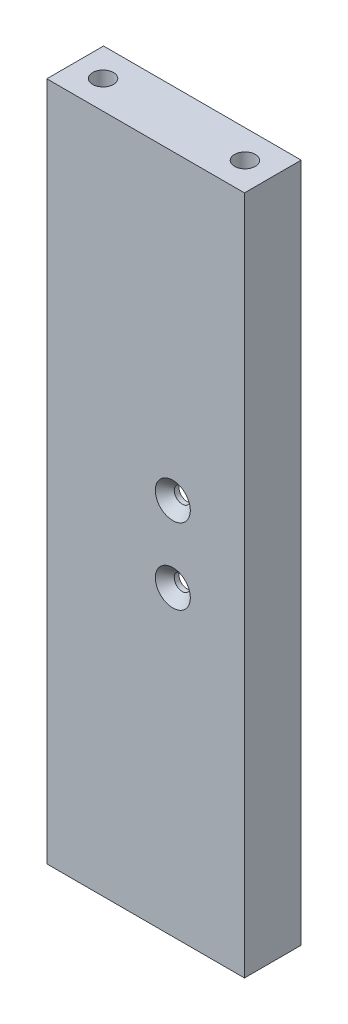
SolidWorks part; units mm, degrees
ref_plane "Front Plane" through (0, 0, 0) normal (0, 0, 1) x (1, 0, 0)
ref_plane "Top Plane" through (0, 0, 0) normal (0, 1, 0) x (1, 0, 0)
ref_plane "Right Plane" through (0, 0, 0) normal (1, 0, 0) x (0, 0, -1)
sketch "Sketch1" plane through (0, 0, 0) normal (0, 0, 1) x (1, 0, 0)
  line L1 (-20.9, 0) -> (20.9, 0)
  line L2 (-20.9, 0) -> (-20.9, 143.8)
  line L3 (-20.9, 143.8) -> (20.9, 143.8)
  line L4 (20.9, 0) -> (20.9, 143.8)
  point P4 (0, 0)
  dimension "D1" = 143.8
  dimension "D2" = 41.8
extrude "Boss-Extrude1" add sketch "Sketch1" against normal blind 12
shell "Shell1" thickness 7
sketch "Sketch2" plane through (0, 143.8, 0) normal (0, 1, 0) x (1, 0, 0)
  line L0 (0, 12) -> (0, 0) construction
  line L1 (20.9, 12) -> (-20.9, 12) construction
  line L5 (20.9, 0) -> (-20.9, 0) construction
  circle A1 centre (-15, 6) radius 2.2
  circle A2 centre (15, 6) radius 2.2
  dimension "D1" = 4.4
  dimension "D2" = 6
  dimension "D3" = 15
extrude "Cut-Extrude1" cut sketch "Sketch2" against normal blind 5.2
ref_plane "Plane1" through (0, 71.9, 0) normal (0, 1, 0) x (1, 0, 0)
mirror "Mirror1" about plane through (0, 71.9, 0) normal (0, 1, 0) of "Cut-Extrude1"
sketch "Sketch3" plane through (-20.9, 0, 0) normal (-1, 0, 0) x (0, 0, 1)
  line L0 (-6, 143.8) -> (-6, 0) construction
  line L1 (-12, 143.8) -> (0, 143.8) construction
  line L2 (-12, 0) -> (0, 0) construction
  line L3 (0, 71.9) -> (-12, 71.9) construction
  line L4 (0, 143.8) -> (0, 0) construction
  line L5 (-12, 143.8) -> (-12, 0) construction
  circle A0 centre (-6, 129.4) radius 2.2
  circle A1 centre (-6, 14.4) radius 2.2
  dimension "D1" = 57.5
  dimension "D2" = 4.4
extrude "Cut-Extrude2" cut sketch "Sketch3" against normal blind 5.2
sketch "Sketch5" plane through (0, 0, -3) normal (0, 0, -1) x (-1, 0, 0)
  line L0 (-13.9, 71.9) -> (13.9, 71.9) construction
  line L1 (-13.9, 7) -> (-13.9, 136.8) construction
  line L2 (13.9, 136.8) -> (13.9, 7) construction
  line L3 (-5.75, 63.9) -> (-5.75, 79.9) construction
  line L4 (8, 61.65) -> (-8, 61.65) construction
  line L5 (8, 61.65) -> (8, 82.15) construction
  line L6 (8, 82.15) -> (-8, 82.15) construction
  line L7 (-8, 61.65) -> (-8, 82.15) construction
  line L8 (8, 61.65) -> (-8, 82.15) construction
  line L9 (8, 82.15) -> (-8, 61.65) construction
  line L10 (0, 71.9) -> (0, 78.707) construction
  circle A0 centre (-5.75, 63.9) radius 1.7
  circle A1 centre (-5.75, 79.9) radius 1.7
  point P6 (0, 71.9)
  point P15 (-5.75, 71.9)
  dimension "D2" = 3.4
  dimension "D5" = 5.75
  dimension "D1" = 16
  dimension "D3" = 16
  dimension "D4" = 20.5
extrude "Cut-Extrude3" cut sketch "Sketch5" against normal blind 10
chamfer "Chamfer1" distance 2 angle 45 2 edges at (4.05, 63.9, 0) (4.05, 79.9, 0)
